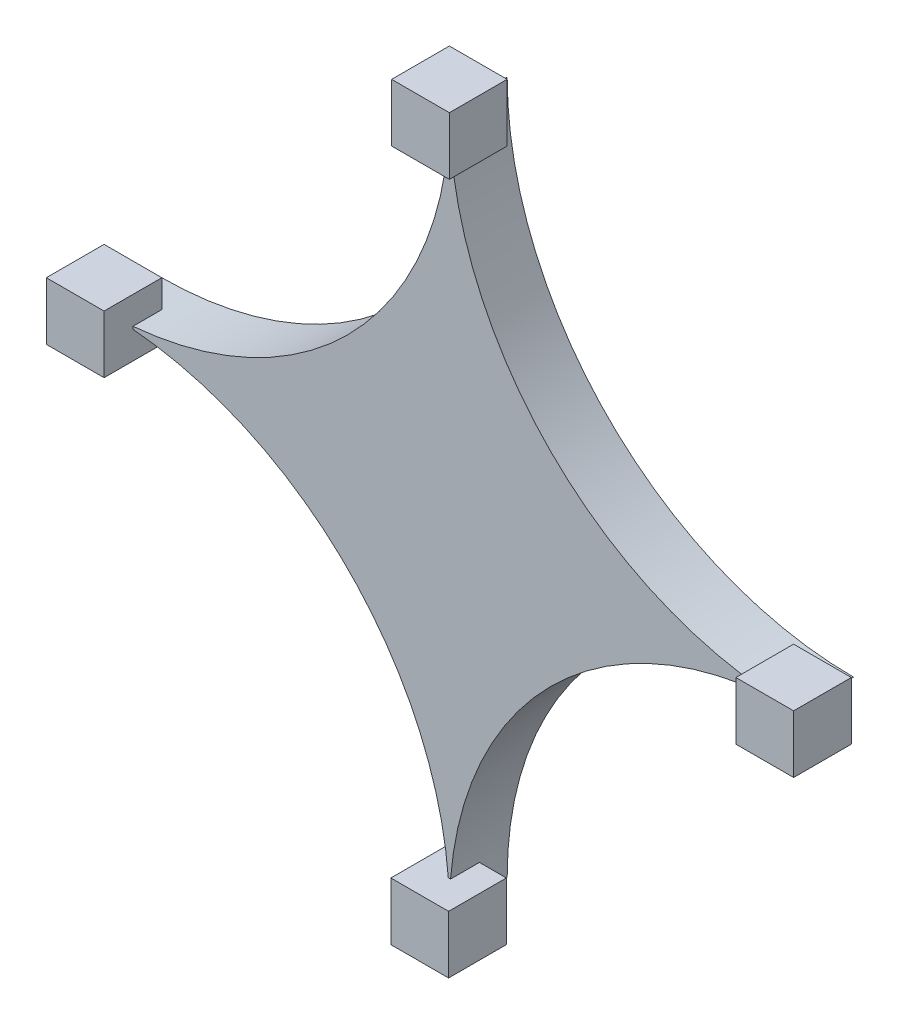
SolidWorks part; units mm, degrees
ref_plane "Front Plane" through (0, 0, 0) normal (0, 0, 1) x (1, 0, 0)
ref_plane "Top Plane" through (0, 0, 0) normal (0, 1, 0) x (1, 0, 0)
ref_plane "Right Plane" through (0, 0, 0) normal (1, 0, 0) x (0, 0, -1)
sketch "Sketch1" plane through (0, 0, 0) normal (0, 0, 1) x (1, 0, 0)
  line L0 (0, 60) -> (0, -60) construction
  line L1 (-60, 0) -> (60, 0) construction
  circle A0 centre (0, 0) radius 15
  arc A1 (0, 60) -> (60, 0) centre (60, 60) ccw
  arc A2 (60, 0) -> (0, -60) centre (60, -60) ccw
  arc A3 (0, -60) -> (-60, 0) centre (-60, -60) ccw
  arc A4 (-60, 0) -> (0, 60) centre (-60, 60) ccw
  dimension "D1" = 30
  dimension "D2" = 120
  dimension "D3" = 120
extrude "Boss-Extrude2" add sketch "Sketch1" along normal blind 10 contours A4 A1 A2 A3
sketch "Sketch2" plane through (0, 0, 10) normal (0, 0, 1) x (1, 0, 0)
  line L1 (4.8586, -55.1798) -> (-5.1414, -55.1798)
  line L2 (4.8586, -55.1798) -> (4.8586, -65.1798)
  line L3 (4.8586, -65.1798) -> (-5.1414, -65.1798)
  line L4 (-5.1414, -55.1798) -> (-5.1414, -65.1798)
  line L5 (4.8586, -55.1798) -> (-5.1414, -65.1798) construction
  line L6 (4.8586, -65.1798) -> (-5.1414, -55.1798) construction
  line L7 (64.6008, 4.7554) -> (54.6008, 4.7554)
  line L8 (64.6008, 4.7554) -> (64.6008, -5.2446)
  line L9 (64.6008, -5.2446) -> (54.6008, -5.2446)
  line L10 (54.6008, 4.7554) -> (54.6008, -5.2446)
  line L11 (64.6008, 4.7554) -> (54.6008, -5.2446) construction
  line L12 (64.6008, -5.2446) -> (54.6008, 4.7554) construction
  line L13 (-64.7983, -4.9904) -> (-54.7983, -4.9904)
  line L14 (-64.7983, -4.9904) -> (-64.7983, 5.0096)
  line L15 (-64.7983, 5.0096) -> (-54.7983, 5.0096)
  line L16 (-54.7983, -4.9904) -> (-54.7983, 5.0096)
  line L17 (-64.7983, -4.9904) -> (-54.7983, 5.0096) construction
  line L18 (-64.7983, 5.0096) -> (-54.7983, -4.9904) construction
  line L19 (4.9929, 64.6513) -> (-5.0071, 64.6513)
  line L20 (4.9929, 64.6513) -> (4.9929, 54.6513)
  line L21 (4.9929, 54.6513) -> (-5.0071, 54.6513)
  line L22 (-5.0071, 64.6513) -> (-5.0071, 54.6513)
  line L23 (4.9929, 64.6513) -> (-5.0071, 54.6513) construction
  line L24 (4.9929, 54.6513) -> (-5.0071, 64.6513) construction
  point P4 (-0.1414, -60.1798)
  point P9 (59.6008, -0.2446)
  point P14 (-59.7983, 0.0096)
  point P19 (-0.0071, 59.6513)
  dimension "D1" = 10
  dimension "D2" = 10
  dimension "D3" = 10
  dimension "D4" = 10
  dimension "D5" = 10
  dimension "D6" = 10
  dimension "D7" = 10
  dimension "D8" = 10
extrude "Boss-Extrude3" add sketch "Sketch2" along normal mid plane 10
